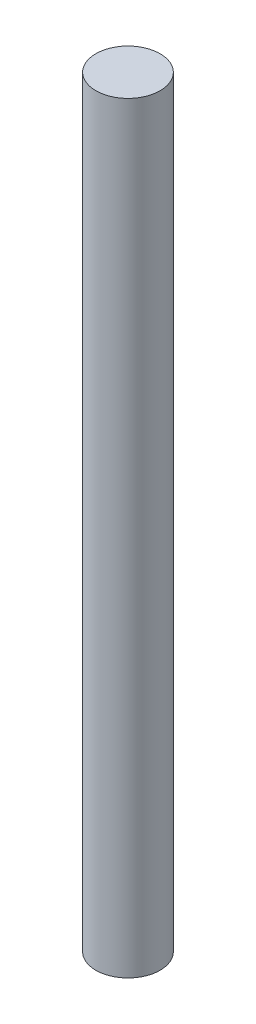
SolidWorks part; units mm, degrees
ref_plane "Front Plane" through (0, 0, 0) normal (0, 0, 1) x (1, 0, 0)
ref_plane "Top Plane" through (0, 0, 0) normal (0, 1, 0) x (1, 0, 0)
ref_plane "Right Plane" through (0, 0, 0) normal (1, 0, 0) x (0, 0, -1)
sketch "Sketch1" plane through (0, 0, 0) normal (0, 1, 0) x (1, 0, 0)
  circle A0 centre (0, 0) radius 1.5
  dimension "D1" = 3
extrude "Boss-Extrude1" add sketch "Sketch1" along normal blind 35.6
